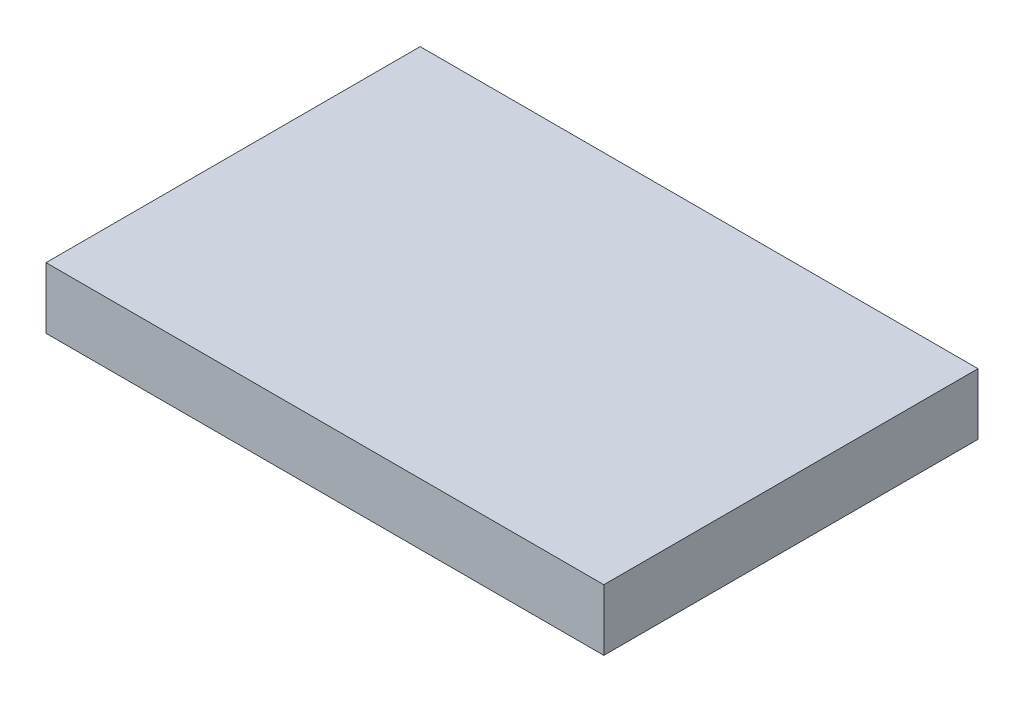
SolidWorks part; units mm, degrees
other "Markup2"
sketch "Sketch3" plane through (41, 9, 27.5) normal (0, 1, 0) x (0, 0, 1)
other "DetailItem2"
ref_plane "Front Plane" through (0, 0, 0) normal (0, 0, 1) x (1, 0, 0)
ref_plane "Top Plane" through (0, 0, 0) normal (0, 1, 0) x (1, 0, 0)
ref_plane "Right Plane" through (0, 0, 0) normal (1, 0, 0) x (0, 0, -1)
sketch "Sketch1" plane through (0, 0, 0) normal (0, 1, 0) x (1, 0, 0)
  line L1 (-41, -27.5) -> (41, -27.5)
  line L2 (-41, -27.5) -> (-41, 27.5)
  line L3 (-41, 27.5) -> (41, 27.5)
  line L4 (41, -27.5) -> (41, 27.5)
  line L5 (-41, -27.5) -> (41, 27.5) construction
  line L6 (-41, 27.5) -> (41, -27.5) construction
  point P0 (0, 0)
  dimension "D1" = 82
  dimension "D2" = 55
extrude "Boss-Extrude1" add sketch "Sketch1" along normal blind 9 contours L3 L4 L1 L2
